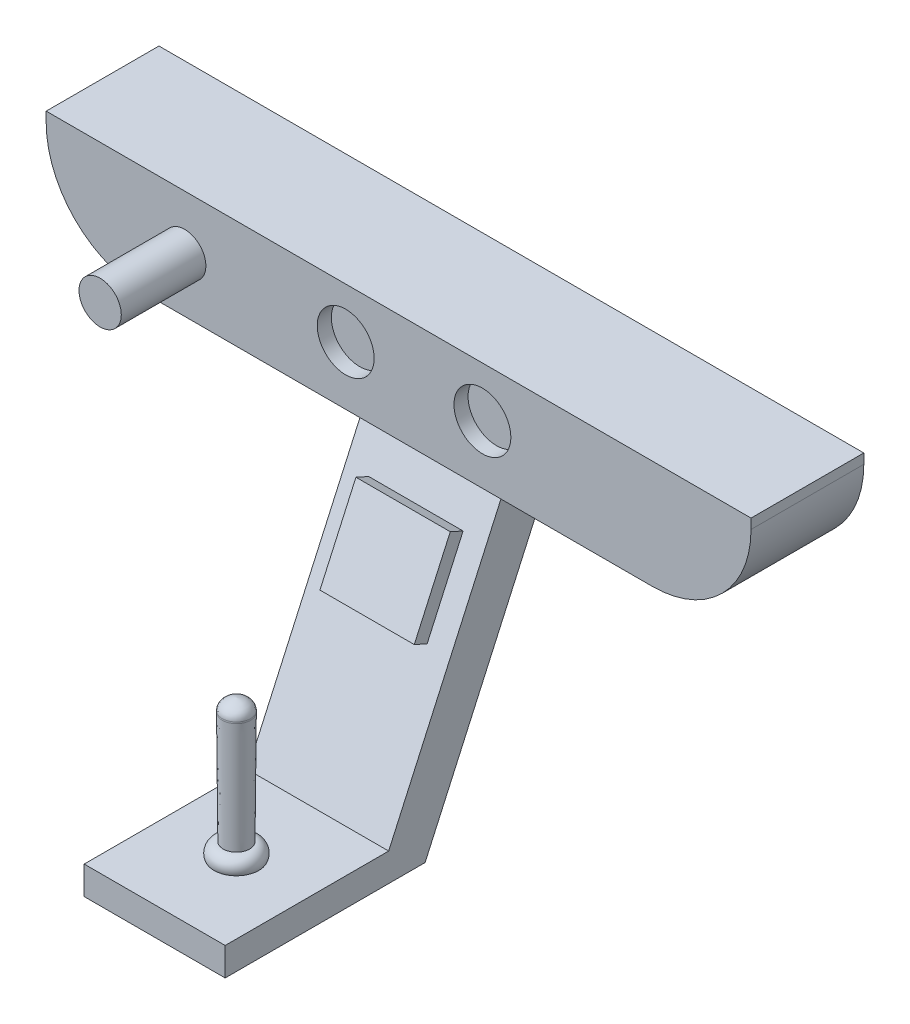
SolidWorks part; units mm, degrees
ref_plane "Front Plane" through (0, 0, 0) normal (0, 0, 1) x (1, 0, 0)
ref_plane "Top Plane" through (0, 0, 0) normal (0, 1, 0) x (1, 0, 0)
ref_plane "Right Plane" through (0, 0, 0) normal (1, 0, 0) x (0, 0, -1)
sketch "Sketch1" plane through (0, 0, 0) normal (0, 0, 1) x (1, 0, 0)
  line L0 (-26.9036, 0) -> (23.0964, 0)
  line L1 (-26.9036, 0) -> (-26.9036, -0.7)
  line L2 (-19.9036, -7.7) -> (16.0964, -7.7)
  line L3 (23.0964, -0.7) -> (23.0964, 0)
  arc A0 (16.0964, -7.7) -> (23.0964, -0.7) centre (16.0964, -0.7) ccw
  arc A1 (-26.9036, -0.7) -> (-19.9036, -7.7) centre (-19.9036, -0.7) ccw
  point P9 (-26.9036, -7.7)
  dimension "D3" = 7
  dimension "D1" = 50
  dimension "D2" = 7.7
extrude "Boss-Extrude1" add sketch "Sketch1" along normal blind 8
sketch "Sketch2" plane through (0, 0, 8) normal (0, 0, 1) x (1, 0, 0)
  circle A1 centre (-17.0762, -3.85) radius 1.5
  dimension "D1" = 3
extrude "Boss-Extrude2" add sketch "Sketch2" along normal blind 6
sketch "Sketch3" plane through (0, 0, 0) normal (1, 0, 0) x (0, 0, -1)
  line L0 (-4, -7.7) -> (-13.0246, -27.7)
  line L1 (-8, -7.7) -> (0, -7.7) construction
  line L2 (-13.0246, -27.7) -> (-25.0246, -27.7)
  line L4 (-25.0246, -25.7) -> (-15.6093, -25.7)
  line L5 (-15.6093, -25.7) -> (-7.4872, -7.7)
  line L6 (-7.4872, -7.7) -> (-4, -7.7)
  line L7 (-25.0246, -25.7) -> (-27.2072, -25.7)
  line L8 (-27.2072, -25.7) -> (-27.2072, -27.7)
  line L9 (-27.2072, -27.7) -> (-25.0246, -27.7)
  dimension "D1" = 2
  dimension "D2" = 20
extrude "Boss-Extrude3" add sketch "Sketch3" along normal mid plane 10
sketch "Sketch6" plane through (0, 1.5044, 3.3339) normal (0, 0.4113, 0.9115) x (1, 0, 0)
  line L1 (-3.3458, -19.1914) -> (3.3458, -19.1914)
  line L2 (-3.3458, -19.1914) -> (-3.3458, -12.9855)
  line L3 (-3.3458, -12.9855) -> (3.3458, -12.9855)
  line L4 (3.3458, -19.1914) -> (3.3458, -12.9855)
  line L5 (-3.3458, -19.1914) -> (3.3458, -12.9855) construction
  line L6 (-3.3458, -12.9855) -> (3.3458, -19.1914) construction
  point P0 (0, -16.0885)
extrude "Boss-Extrude6" add sketch "Sketch6" along normal blind 1
sketch "Sketch7" plane through (0, 0, 8) normal (0, 0, 1) x (1, 0, 0)
  circle A0 centre (-5.6576, -3.5623) radius 2.0184
  circle A1 centre (4.0404, -3.5623) radius 2.0184
extrude "Cut-Extrude1" cut sketch "Sketch7" against normal blind 1
sketch "Sketch10" plane through (0, 0, 0) normal (1, 0, 0) x (0, 0, -1)
  line L0 (-21.4082, -25.7) -> (-21.4082, -15.8737)
  line L1 (-15.6093, -25.7) -> (-27.2072, -25.7) construction
  line L2 (-22.4082, -16.7711) -> (-22.3422, -24.7124)
  line L3 (-22.4082, -16.6664) -> (-22.4082, -16.7711)
  line L4 (-22.997, -25.7) -> (-21.4082, -25.7)
  arc A0 (-22.3422, -24.7124) -> (-22.997, -25.7) centre (-22.3362, -25.4273) ccw
  spline S0 degree 2 poles (-21.4082, -15.8737) (-22.4493, -16.0609) (-22.4082, -16.7711) knots 0 0 0 1 1 1
  dimension "D1" = 1
revolve "Revolve2" add sketch "Sketch10" angle 360 about L0
